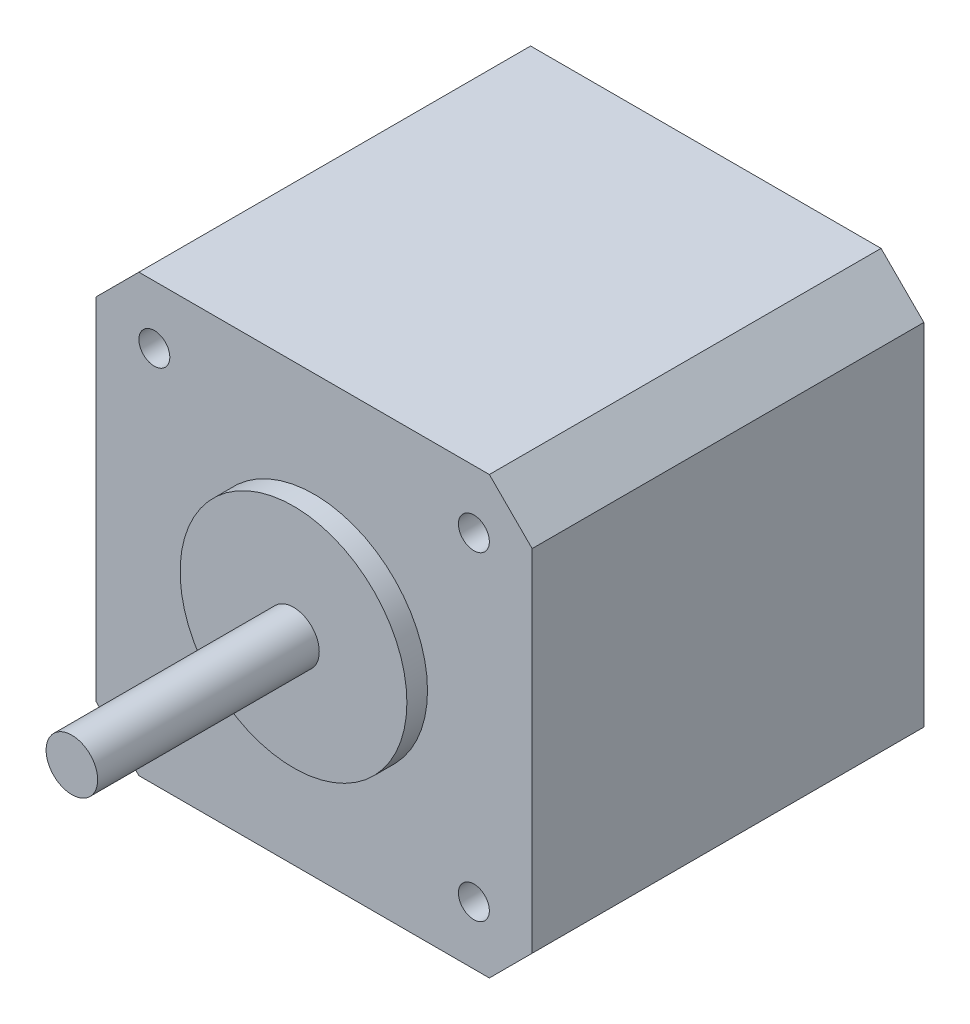
SolidWorks part; units mm, degrees
ref_plane "前视基准面" through (0, 0, 0) normal (0, 0, 1) x (1, 0, 0)
ref_plane "上视基准面" through (0, 0, 0) normal (0, 1, 0) x (1, 0, 0)
ref_plane "右视基准面" through (0, 0, 0) normal (1, 0, 0) x (0, 0, -1)
sketch "草图1" plane through (0, 0, 0) normal (0, 0, 1) x (1, 0, 0)
  line L0 (-39.2214, 9.245) -> (-35.0714, 13.395)
  line L5 (-35.0714, 13.395) -> (-1.0714, 13.395)
  line L7 (-39.2214, 9.245) -> (-39.2214, -24.755)
  line L8 (-35.0714, -28.905) -> (-1.0714, -28.905)
  line L9 (3.0786, 9.245) -> (3.0786, -24.755)
  line L10 (-1.0714, 13.395) -> (3.0786, 9.245)
  line L11 (-39.2214, -24.755) -> (-35.0714, -28.905)
  line L12 (3.0786, -24.755) -> (-1.0714, -28.905)
  dimension "D3" = 34
  dimension "D1" = 42.3
  dimension "D2" = 42.3
  dimension "D5" = 45
  dimension "D6" = 45
extrude "凸台-拉伸1" add sketch "草图1" along normal blind 38
sketch "草图2" plane through (0, 0, 38) normal (0, 0, 1) x (1, 0, 0)
  line L0 (3.0786, -24.755) -> (3.0786, 9.245) construction
  line L1 (-35.0714, -28.905) -> (-1.0714, -28.905) construction
  line L2 (-39.2214, -7.755) -> (3.0786, -7.755) construction
  line L3 (-39.2214, 9.245) -> (-39.2214, -24.755) construction
  line L4 (-18.0714, 13.395) -> (-18.0714, -28.905) construction
  line L5 (-1.0714, 13.395) -> (-35.0714, 13.395) construction
  circle A0 centre (-18.0714, -7.755) radius 11
  point P10 (-18.0714, -7.755)
  point P11 (-18.0714, -7.755)
  point P12 (3.0786, -7.755)
  point P15 (-18.0714, -28.905)
  point P18 (0, 0)
  dimension "D1" = 22
extrude "凸台-拉伸2" add sketch "草图2" along normal blind 2
sketch "草图3" plane through (0, 0, 40) normal (0, 0, 1) x (1, 0, 0)
  circle A0 centre (-18.0714, -7.755) radius 2.5
  circle A1 centre (-18.0714, -7.755) radius 11 construction
  point P2 (-16.4125, -10.7251)
  point P3 (0, 0)
  point P4 (0, 0)
  dimension "D1" = 5
extrude "凸台-拉伸3" add sketch "草图3" along normal blind 21.5
sketch "草图4" plane through (0, 0, 0) normal (0, 0, -1) x (-1, 0, 0)
  line L0 (-3.0786, -7.755) -> (39.2214, -7.755) construction
  line L1 (-3.0786, -24.755) -> (-3.0786, 9.245) construction
  line L2 (39.2214, 9.245) -> (39.2214, -24.755) construction
  line L3 (18.0714, 13.395) -> (18.0714, -28.905) construction
  line L4 (1.0714, 13.395) -> (35.0714, 13.395) construction
  line L5 (35.0714, -28.905) -> (1.0714, -28.905) construction
  circle A0 centre (2.5714, 7.745) radius 1.5
  circle A1 centre (2.5714, -23.255) radius 1.5
  circle A2 centre (33.5714, -23.255) radius 1.5
  circle A3 centre (33.5714, 7.745) radius 1.5
  dimension "D3" = 3
  dimension "D1" = 31
  dimension "D2" = 31
extrude "切除-拉伸1" cut sketch "草图4" against normal up to next
